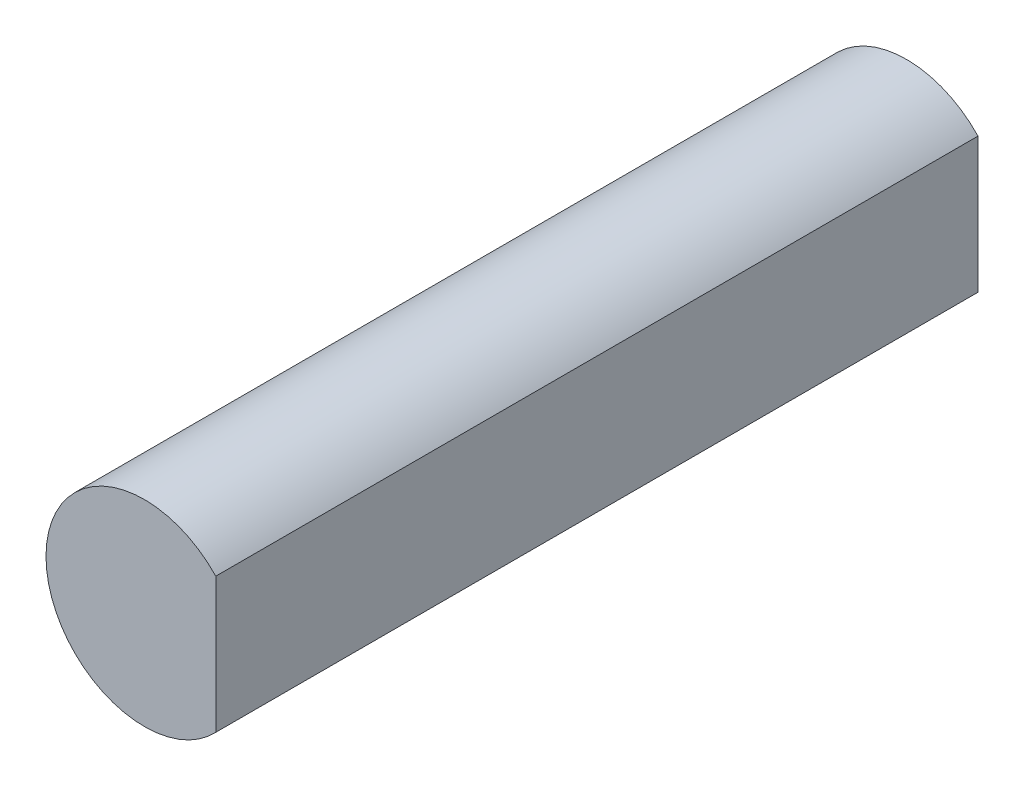
SolidWorks part; units mm, degrees
ref_plane "Alzado" through (0, 0, 0) normal (0, 0, 1) x (1, 0, 0)
ref_plane "Planta" through (0, 0, 0) normal (0, 1, 0) x (1, 0, 0)
ref_plane "Vista lateral" through (0, 0, 0) normal (1, 0, 0) x (0, 0, -1)
sketch "Croquis1" plane through (0, 0, 0) normal (0, 0, 1) x (1, 0, 0)
  line L0 (2, 1.5) -> (2, -1.5)
  line L1 (2.9047, 2.75) -> (2.9047, -2.75)
  arc A0 (2, 1.5) -> (2, -1.5) centre (0, 0) ccw
  arc A1 (2.9047, 2.75) -> (2.9047, -2.75) centre (0, 0) ccw
  dimension "D2" = 5
  dimension "D3" = 8
  dimension "D1" = 3
  dimension "D4" = 5.5
extrude "Saliente-Extruir1" add sketch "Croquis1" along normal blind 31
sketch "Croquis2" plane through (0, 0, 31) normal (0, 0, 1) x (1, 0, 0)
  line L0 (2.9047, 2.75) -> (2.9047, -2.75)
  arc A0 (2.9047, 2.75) -> (2.9047, -2.75) centre (0, 0) ccw
extrude "Saliente-Extruir2" add sketch "Croquis2" against normal blind 6.2
sketch "Croquis5" plane through (0, 0, 0) normal (0, 0, -1) x (-1, 0, 0)
  circle A0 centre (0, 0) radius 2.5
extrude "Cortar-Extruir1" cut sketch "Croquis5" against normal blind 5
